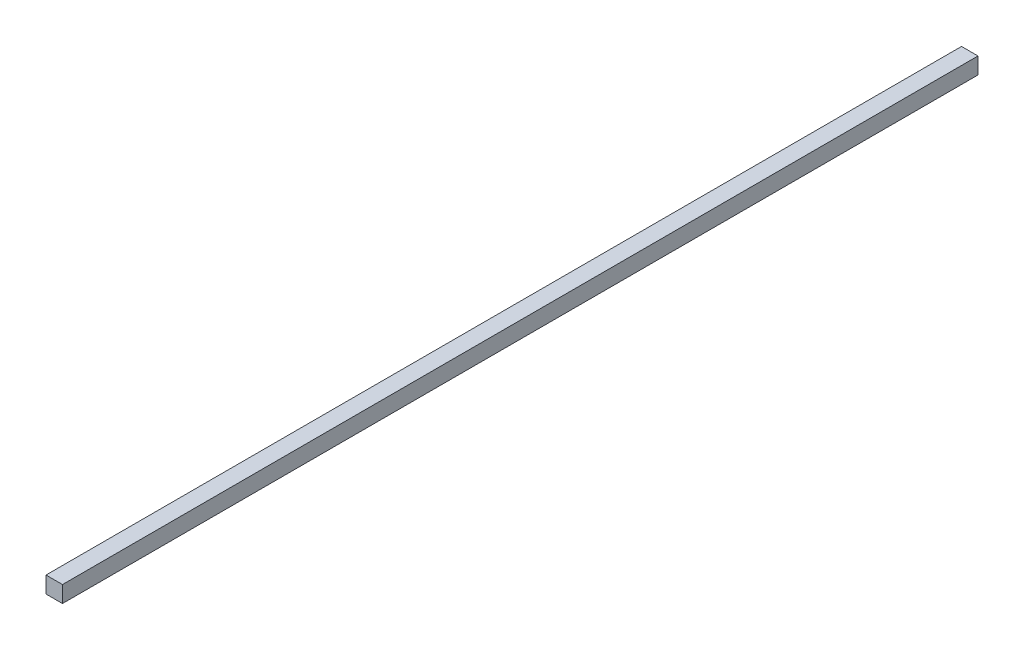
SolidWorks part; units mm, degrees
ref_plane "Front" through (0, 0, 0) normal (0, 0, 1) x (1, 0, 0)
ref_plane "Top" through (0, 0, 0) normal (0, 1, 0) x (1, 0, 0)
ref_plane "Right" through (0, 0, 0) normal (1, 0, 0) x (0, 0, -1)
other "Configuration Table"
sketch "Sketch1" plane through (0, 0, 0) normal (0, 0, 1) x (1, 0, 0)
  line L1 (0, 0) -> (22.86, 0)
  line L2 (0, 0) -> (0, 22.86)
  line L3 (0, 22.86) -> (22.86, 22.86)
  line L4 (22.86, 0) -> (22.86, 22.86)
  dimension "D1" = 22.86
extrude "Extrude1" add sketch "Sketch1" along normal blind 1270
